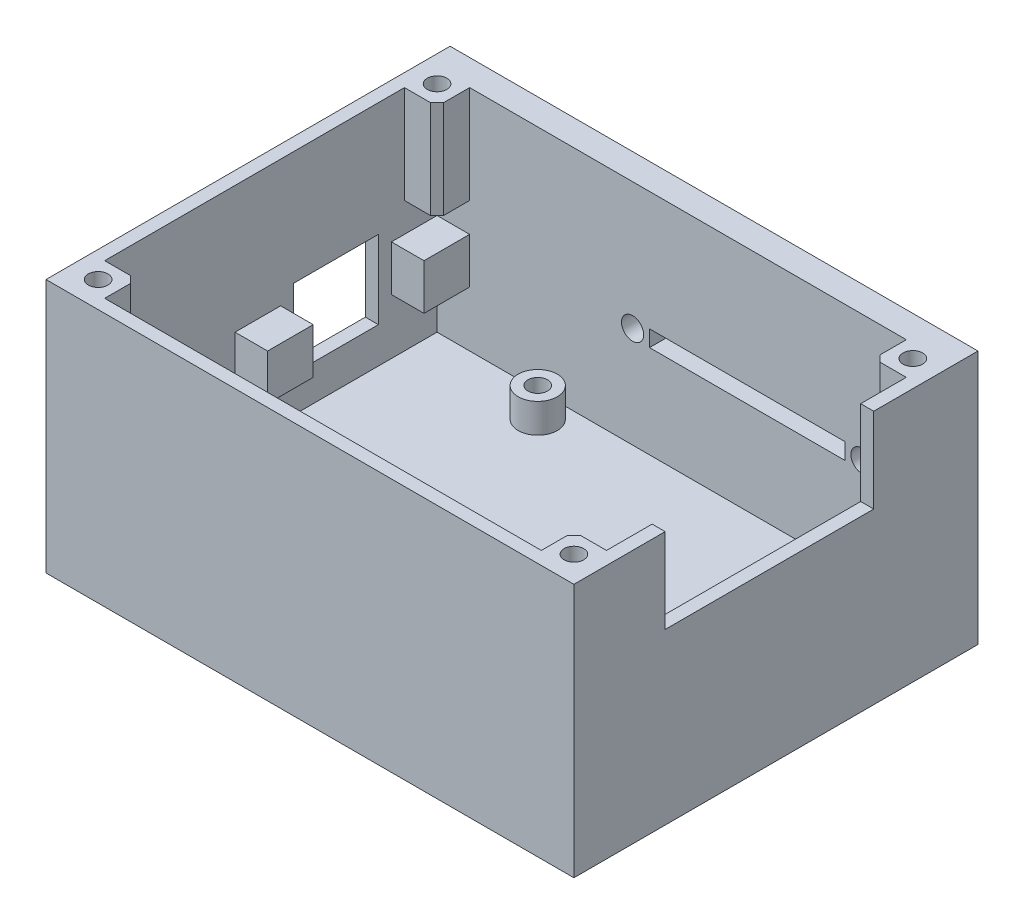
SolidWorks part; units mm, degrees
ref_plane "Ebene vorne" through (0, 0, 0) normal (0, 0, 1) x (1, 0, 0)
ref_plane "Ebene oben" through (0, 0, 0) normal (0, 1, 0) x (1, 0, 0)
ref_plane "Ebene rechts" through (0, 0, 0) normal (1, 0, 0) x (0, 0, -1)
sketch "Sketch1" plane through (0, 0, 0) normal (0, 1, 0) x (1, 0, 0)
  line L1 (-40.5, -30) -> (40.5, -30)
  line L2 (-40.5, -30) -> (-40.5, 32)
  line L3 (-40.5, 32) -> (40.5, 32)
  line L4 (40.5, -30) -> (40.5, 32)
  line L7 (-40.5, 26.65) -> (34.3, 26.65) construction
  line L8 (-40.5, 26.65) -> (-40.5, -26.65) construction
  line L9 (-40.5, -26.65) -> (34.3, -26.65) construction
  line L10 (34.3, 26.65) -> (34.3, -26.65) construction
  line L15 (-40.5, -30) -> (-30.5, -30)
  line L16 (-40.5, -30) -> (-40.5, -40)
  point P0 (0, 0)
  dimension "D1" = 62
  dimension "D2" = 81
  dimension "D3" = 74.8
  dimension "D4" = 53.3
  dimension "D5" = 26.65
  dimension "D6" = 30
extrude "Extrude1" add sketch "Sketch1" along normal blind 4
sketch "Sketch2" plane through (0, 4, 0) normal (0, 1, 0) x (1, 0, 0)
  line L1 (-40.5, 32) -> (40.5, 32)
  line L2 (-40.5, 32) -> (-40.5, 28)
  line L3 (-40.5, 28) -> (40.5, 28)
  line L4 (40.5, 32) -> (40.5, 28)
  line L6 (40.5, 32) -> (38.5, 32)
  line L7 (40.5, 32) -> (40.5, -30)
  line L8 (40.5, -30) -> (38.5, -30)
  line L9 (38.5, 32) -> (38.5, -30)
  line L11 (40.5, -30) -> (-40.5, -30)
  line L12 (40.5, -30) -> (40.5, -28)
  line L13 (40.5, -28) -> (-40.5, -28)
  line L14 (-40.5, -30) -> (-40.5, -28)
  line L16 (-40.5, 32) -> (-38.5, 32)
  line L17 (-40.5, 32) -> (-40.5, -30)
  line L18 (-40.5, -30) -> (-38.5, -30)
  line L19 (-38.5, 32) -> (-38.5, -30)
  dimension "D1" = 2
  dimension "D2" = 4
  dimension "D3" = 2
  dimension "D4" = 2
extrude "Extrude2" add sketch "Sketch2" along normal blind 35
sketch "Sketch3" plane through (0, 4, 0) normal (0, 1, 0) x (1, 0, 0)
  line L0 (-40.5, 32) -> (-40.5, -30) construction
  circle A0 centre (-19.2, 24.15) radius 3
  circle A1 centre (-20.3, -23.65) radius 3
  circle A2 centre (31.6, -18.95) radius 3
  circle A4 centre (31.6, 8.95) radius 3
  dimension "D1" = 21.3
  dimension "D3" = 1.1
  dimension "D5" = 4.7
  dimension "D6" = 27.9
  dimension "D9" = 6
  dimension "D2" = 24.15
  dimension "D4" = 47.8
  dimension "D7" = 50.8
  dimension "D8" = 51.9
extrude "Extrude3" add sketch "Sketch3" along normal blind 4.5 contours A2 | A1 | A0 | A4
sketch "Sketch4" plane through (0, 8.5, 0) normal (0, 1, 0) x (1, 0, 0)
  circle A0 centre (-19.2, 24.15) radius 1.5
  circle A1 centre (31.6, 8.95) radius 1.5
  circle A2 centre (31.6, -18.95) radius 1.5
  circle A3 centre (-20.3, -23.65) radius 1.5
  dimension "D1" = 3
  dimension "D2" = 3
  dimension "D3" = 3
  dimension "D4" = 3
extrude "Extrude4" cut sketch "Sketch4" against normal blind 4.5
sketch "Sketch5" plane through (-40.5, 0, 0) normal (-1, 0, 0) x (0, 0, 1)
  line L1 (-6, 9.5) -> (-19, 9.5)
  line L2 (-6, 9.5) -> (-6, 21.5)
  line L3 (-6, 21.5) -> (-19, 21.5)
  line L4 (-19, 9.5) -> (-19, 21.5)
  line L8 (30, 0) -> (-32, 0) construction
  circle A0 centre (-0.5, 16) radius 1.25
  circle A1 centre (-24.5, 16) radius 1.25
  dimension "D5" = 5.5
  dimension "D7" = 2.5
  dimension "D1" = 6
  dimension "D2" = 13
  dimension "D3" = 12
  dimension "D4" = 9.5
  dimension "D6" = 5.5
  dimension "D9" = 16
extrude "Extrude5" cut sketch "Sketch5" against normal blind 8 and the other way through all
sketch "Sketch6" plane through (40.5, 0, 0) normal (1, 0, 0) x (0, 0, -1)
  line L1 (-16, 39) -> (16, 39)
  line L2 (-16, 39) -> (-16, 26)
  line L3 (-16, 26) -> (16, 26)
  line L4 (16, 39) -> (16, 26)
  line L5 (-16, 39) -> (16, 26) construction
  line L6 (-16, 26) -> (16, 39) construction
  point P0 (0, 32.5)
  dimension "D1" = 32
  dimension "D2" = 13
extrude "Extrude6" cut sketch "Sketch6" against normal up to next
sketch "Sketch8" plane through (0, 0, 0) normal (0, 1, 0) x (1, 0, 0)
  line L1 (-38.5, 28) -> (-33.5, 28)
  line L2 (-38.5, 28) -> (-38.5, 23)
  line L3 (-38.5, 23) -> (-33.5, 23)
  line L4 (-33.5, 28) -> (-33.5, 23)
  line L5 (-38.5, -28) -> (-33.5, -28)
  line L6 (-38.5, -28) -> (-38.5, -23)
  line L7 (-38.5, -23) -> (-33.5, -23)
  line L8 (-33.5, -28) -> (-33.5, -23)
  line L9 (38.5, -28) -> (-38.5, -28) construction
  line L11 (38.5, 28) -> (33.5, 28)
  line L12 (38.5, 28) -> (38.5, 23)
  line L13 (38.5, 23) -> (33.5, 23)
  line L14 (33.5, 28) -> (33.5, 23)
  line L15 (38.5, -28) -> (33.5, -28)
  line L16 (38.5, -28) -> (38.5, -23)
  line L17 (38.5, -23) -> (33.5, -23)
  line L18 (33.5, -28) -> (33.5, -23)
  dimension "D1" = 5
  dimension "D2" = 5
  dimension "D3" = 5
  dimension "D4" = 5
extrude "Extrude12" add sketch "Sketch8" along direction (0, 1, 0) on the side of the normal blind 15 from offset 24
sketch "Sketch10" plane through (0, 39, 0) normal (0, 1, 0) x (1, 0, 0)
  line L8 (-33.5, 23) -> (-33.5, 28) construction
  line L9 (-38.5, 23) -> (-33.5, 23) construction
  line L10 (33.5, 28) -> (33.5, 23) construction
  line L11 (33.5, 23) -> (38.5, 23) construction
  line L12 (38.5, -23) -> (33.5, -23) construction
  line L13 (33.5, -23) -> (33.5, -28) construction
  line L14 (-33.5, -28) -> (-33.5, -23) construction
  line L15 (-33.5, -23) -> (-38.5, -23) construction
  circle A0 centre (-36.5, 26) radius 1.5
  circle A1 centre (36.5, 26) radius 1.5
  circle A2 centre (36.5, -26) radius 1.5
  circle A3 centre (-36.5, -26) radius 1.5
  point P22 (0, 0)
  point P24 (-37.0218, -29.0027)
  dimension "D1" = 3
  dimension "D4" = 3
  dimension "D7" = 3
  dimension "D10" = 3
  dimension "D2" = 3
  dimension "D3" = 3
  dimension "D5" = 3
  dimension "D6" = 3
  dimension "D8" = 3
  dimension "D9" = 3
  dimension "D11" = 3
  dimension "D12" = 3
extrude "Extrude13" cut sketch "Sketch10" against normal blind 10
chamfer "Chamfer5" distance 1 4 edges at (33.5, 31.5, 23) (-33.5, 31.5, 23) (-33.5, 31.5, -23) (33.5, 31.5, -23)
sketch "Sketch12" plane through (0, 0, -32) normal (0, 0, -1) x (-1, 0, 0)
  line L0 (-40.5, 39) -> (40.5, 39) construction
  line L1 (40.5, 39) -> (40.5, 0) construction
  line L6 (-24.1, 18.25) -> (5.9, 18.25)
  line L7 (-24.1, 18.25) -> (-24.1, 20.75)
  line L8 (-24.1, 20.75) -> (5.9, 20.75)
  line L9 (5.9, 18.25) -> (5.9, 20.75)
  line L10 (-24.1, 18.25) -> (5.9, 20.75) construction
  line L11 (-24.1, 20.75) -> (5.9, 18.25) construction
  circle A0 centre (-26.7, 19.5) radius 1.7
  circle A1 centre (8.5, 19.5) radius 1.7
  point P5 (0, 0)
  point P7 (-9.1, 19.5)
  point P12 (0, 0)
  point P13 (0, 0)
  point P16 (0, 0)
  point P18 (18.0163, 18.9407)
  dimension "D1" = 35.2
  dimension "D2" = 3.4
  dimension "D3" = 19.5
  dimension "D4" = 17.6
  dimension "D5" = 2.5
  dimension "D6" = 30
  dimension "D7" = 32
extrude "Extrude15" cut sketch "Sketch12" against normal blind 4
sketch "Sketch13" plane through (-38.5, 0, 0) normal (1, 0, 0) x (0, 0, -1)
  line L14 (4, 12.5) -> (-3, 12.5)
  line L15 (28, 12.5) -> (21, 12.5)
  line L16 (28, 12.5) -> (28, 19.5)
  line L17 (28, 19.5) -> (21, 19.5)
  line L18 (21, 12.5) -> (21, 19.5)
  line L19 (28, 12.5) -> (21, 19.5) construction
  line L20 (28, 19.5) -> (21, 12.5) construction
  line L21 (4, 12.5) -> (4, 19.5)
  line L22 (4, 19.5) -> (-3, 19.5)
  line L23 (-3, 12.5) -> (-3, 19.5)
  line L24 (4, 12.5) -> (-3, 19.5) construction
  line L25 (4, 19.5) -> (-3, 12.5) construction
  point P0 (0.5133, 15.9037)
  point P1 (0.5, 16)
  point P5 (24.5, 16)
  dimension "D1" = 7
  dimension "D2" = 7
extrude "Extrude16" add sketch "Sketch13" along normal blind 5
sketch "Sketch14" plane through (-38.5, 0, 0) normal (-1, 0, 0) x (0, 0, 1)
  circle A0 centre (-0.5, 16) radius 1.25
  circle A1 centre (-24.5, 16) radius 1.25
  dimension "D1" = 2.5
  dimension "D2" = 2.5
extrude "Extrude17" cut sketch "Sketch14" against normal blind 3
sketch "Sketch15" plane through (0, 0, 0) normal (0, -1, 0) x (1, 0, 0)
  line L0 (-40.5, 30) -> (-40.5, -32) construction
  line L1 (-40.5, 24.1848) -> (40.5, 24.1848) construction
  line L2 (-40.5, 24.1848) -> (-40.5, 10) construction
  line L3 (-40.5, 10) -> (40.5, 10) construction
  line L4 (40.5, 24.1848) -> (40.5, 10) construction
  line L5 (40.5, 30) -> (40.5, -32) construction
  line L7 (-40.5, -23.0504) -> (40.5, -23.0504) construction
  line L8 (-40.5, -23.0504) -> (-40.5, -12) construction
  line L9 (-40.5, -12) -> (40.5, -12) construction
  line L10 (40.5, -23.0504) -> (40.5, -12) construction
  line L11 (-40.5, -32) -> (40.5, -32) construction
  line L12 (-40.5, 30) -> (40.5, 30) construction
  text T0 "<b>CAN</b>" font "Century Gothic" height 20
  dimension "D1" = 20
  dimension "D2" = 20
extrude "Extrude18" cut sketch "Sketch15" against normal blind 1
